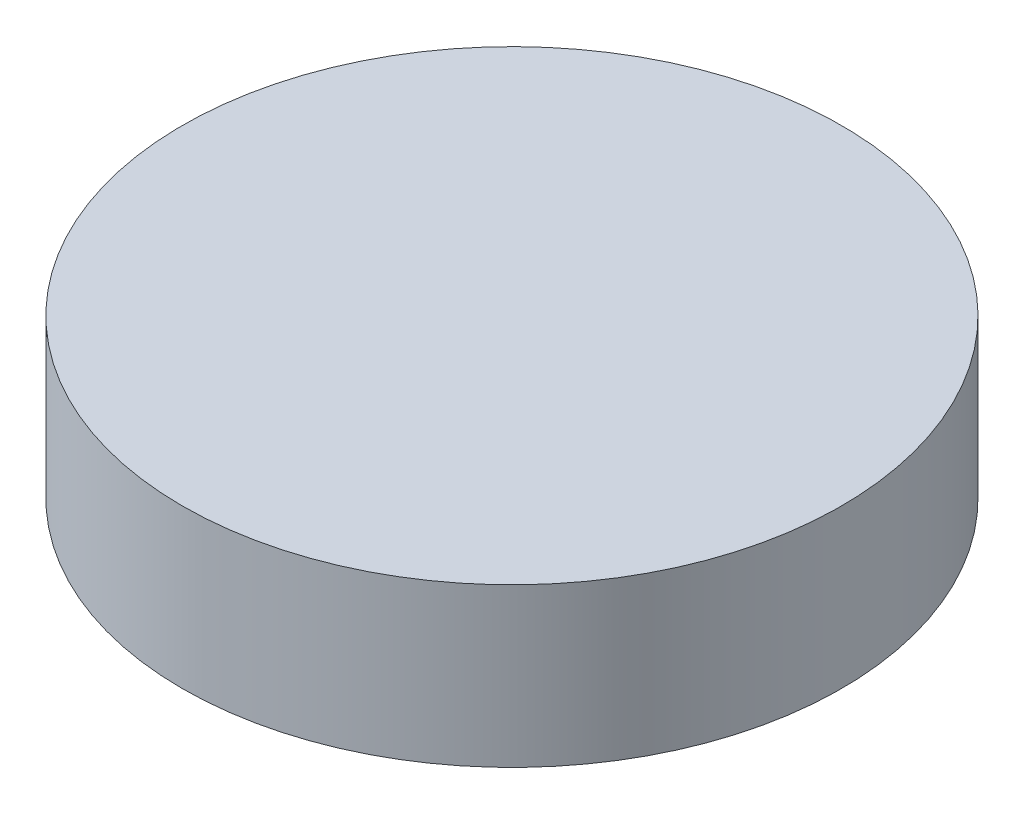
SolidWorks part; units mm, degrees
ref_plane "Front Plane" through (0, 0, 0) normal (0, 0, 1) x (1, 0, 0)
ref_plane "Top Plane" through (0, 0, 0) normal (0, 1, 0) x (1, 0, 0)
ref_plane "Right Plane" through (0, 0, 0) normal (1, 0, 0) x (0, 0, -1)
other "Configuration Table"
sketch "Sketch1" plane through (0, 0, 0) normal (0, 1, 0) x (1, 0, 0)
  circle A0 centre (50, 770) radius 25
extrude "TOPPING_ayar_ayagi_3" add sketch "Sketch1" along normal blind 12 separate body
